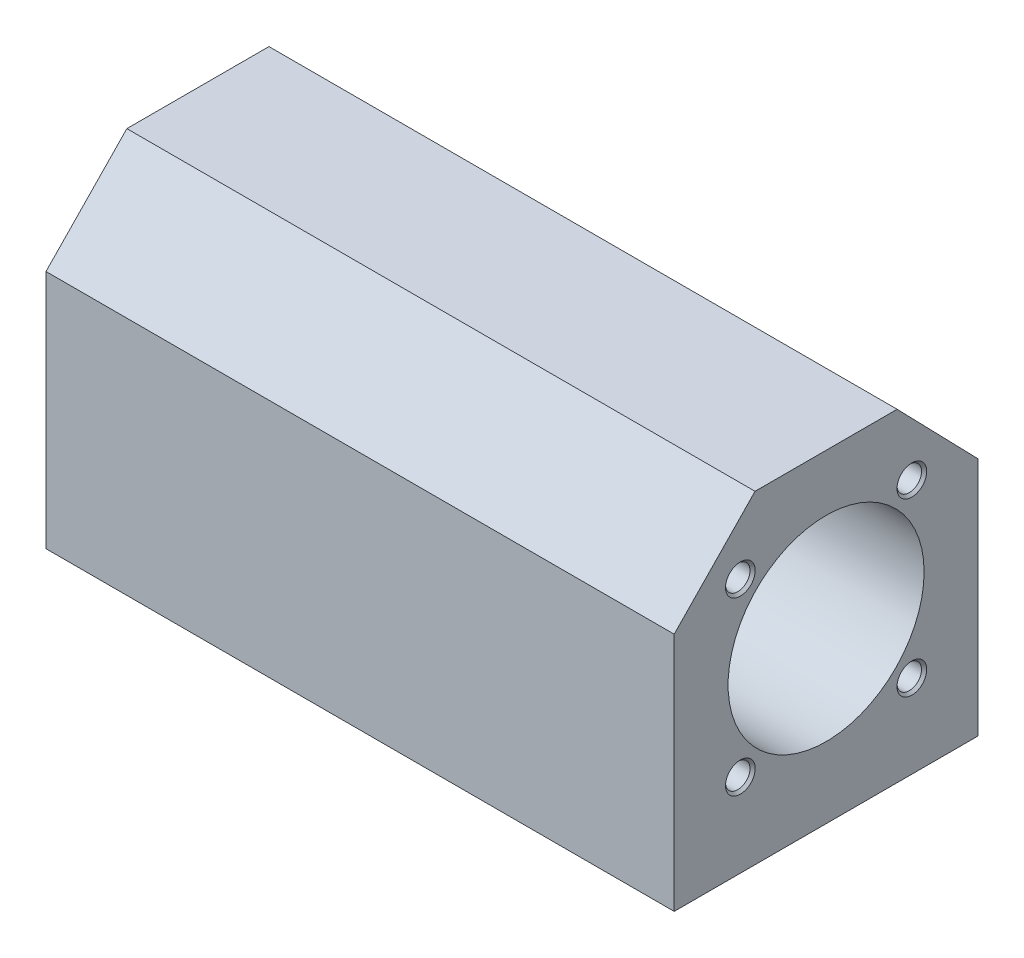
SolidWorks part; units mm, degrees
ref_plane "Plano frontal" through (0, 0, 0) normal (0, 0, 1) x (1, 0, 0)
ref_plane "Plano superior" through (0, 0, 0) normal (0, 1, 0) x (1, 0, 0)
ref_plane "Plano direito" through (0, 0, 0) normal (1, 0, 0) x (0, 0, -1)
sketch "Esboço1" plane through (0, 0, 0) normal (1, 0, 0) x (0, 0, -1)
  line L0 (0, 49) -> (16.5, 66)
  line L1 (0, 0) -> (62, 0)
  line L2 (0, 0) -> (0, 49)
  line L4 (62, 0) -> (62, 49)
  line L5 (16.5, 66) -> (45.5, 66)
  line L6 (45.5, 66) -> (62, 49)
  line L7 (31, 0) -> (31, 66) construction
  point P5 (31, 66)
  dimension "D1" = 66
  dimension "D2" = 49
  dimension "D3" = 62
  dimension "D4" = 29
extrude "Ressalto-extrusão1" add sketch "Esboço1" against normal blind 128.2
hole_wizard "Furo roscado de M61" positions "Esboço2" profile "Esboço3" tap size "M6" standard "ISO"
sketch "Esboço2" plane through (0, 0, 0) normal (1, 0, 0) x (0, 0, -1)
  line L0 (0, 0) -> (62, 0) construction
  line L1 (45.5, 66) -> (16.5, 66) construction
  point P0 (13.5, 52)
  point P2 (48.5, 52)
  point P4 (48.5, 17)
  point P6 (13.5, 17)
  point P14 (31, 66)
  dimension "D1" = 35
  dimension "D2" = 35
  dimension "D3" = 17
  dimension "D4" = 17.5
sketch "Esboço3" plane through (0, 52, -13.5) normal (0, 1, 0) x (0, 0, -1)
  line L0 (0, 0) -> (0, 21.9522)
  line L1 (0, 21.9522) -> (2.5, 20.45)
  line L2 (2.5, 20.45) -> (2.5, 0.525)
  line L3 (2.5, 0.525) -> (3.025, 0)
  line L5 (3.025, 0) -> (0, 0)
  line L6 (-2.5, 0.525) -> (-3.025, 0) construction
  line L10 (0, 21.9522) -> (-2.5, 20.45) construction
  line L11 (0, -6.35) -> (0, 107.95) construction
  dimension "Tap Drill Dia." = 5
  dimension "Tap Drill Depth" = 20.45
  dimension "Near C'Sink Dia." = 6.05
  dimension "Near C'Sink Angle" = 90
  dimension "Drill Angle" = 118
sketch "Esboço4" plane through (0, 0, 0) normal (1, 0, 0) x (0, 0, -1)
  circle A0 centre (31, 34.5) radius 12.5
  circle A1 centre (13.5, 52) radius 2.5 construction
  circle A2 centre (48.5, 17) radius 3.025 construction
  dimension "D1" = 25
  dimension "D2" = 17.5
  dimension "D3" = 17.5
extrude "Corte-extrusão1" cut sketch "Esboço4" against normal through all
sketch "Esboço5" plane through (-128.2, 0, 0) normal (-1, 0, 0) x (0, 0, 1)
  circle A0 centre (-31, 34.5) radius 29
  circle A1 centre (-31, 34.5) radius 12.5 construction
  dimension "D1" = 58
extrude "Corte-extrusão2" cut sketch "Esboço5" against normal blind 50
sketch "Esboço6" plane through (0, 0, 0) normal (1, 0, 0) x (0, 0, -1)
  circle A0 centre (31, 34.5) radius 20
  dimension "D1" = 40
extrude "Corte-extrusão3" cut sketch "Esboço6" against normal blind 70
